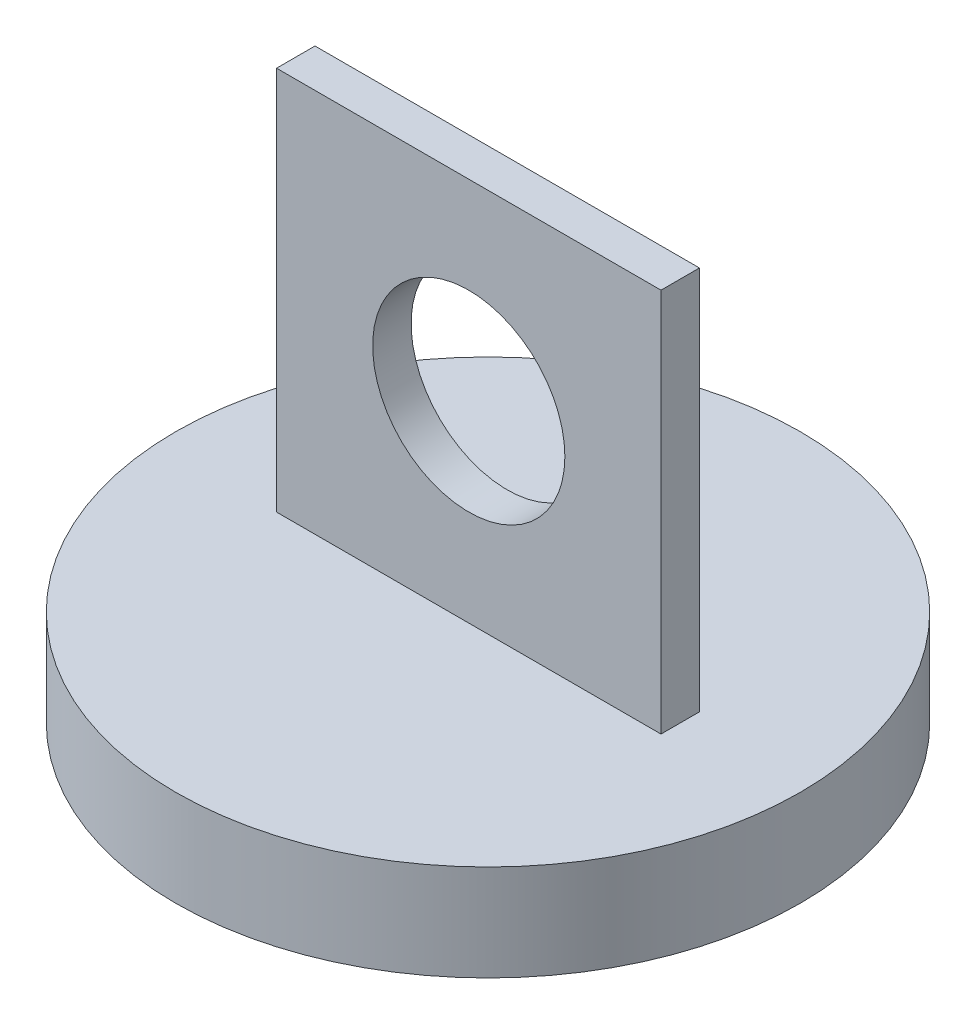
SolidWorks part; units mm, degrees
ref_plane "Front Plane" through (0, 0, 0) normal (0, 0, 1) x (1, 0, 0)
ref_plane "Top Plane" through (0, 0, 0) normal (0, 1, 0) x (1, 0, 0)
ref_plane "Right Plane" through (0, 0, 0) normal (1, 0, 0) x (0, 0, -1)
sketch "Sketch1" plane through (0, 0, 0) normal (0, 1, 0) x (1, 0, 0)
  line L2 (-32.5, 0) -> (75, 0) construction
  circle A1 centre (0, 0) radius 32.5
  dimension "D2" = 65
extrude "Boss-Extrude1" add sketch "Sketch1" along normal blind 10
sketch "Sketch4" plane through (0, 10, 0) normal (0, 1, 0) x (1, 0, 0)
  line L0 (20, 2) -> (-20, 2)
  line L1 (20, 2) -> (20, -2)
  line L2 (20, -2) -> (-20, -2)
  line L3 (-20, 2) -> (-20, -2)
  line L4 (20, 2) -> (-20, -2) construction
  line L5 (20, -2) -> (-20, 2) construction
  point P0 (0, 0)
  dimension "D1" = 4
  dimension "D2" = 40
extrude "Boss-Extrude3" add sketch "Sketch4" along normal blind 40
sketch "Sketch5" plane through (0, 0, 2) normal (0, 0, 1) x (1, 0, 0)
  line L0 (-20, 50) -> (20, 50) construction
  line L1 (20, 50) -> (20, 10) construction
  circle A0 centre (0, 30) radius 10
  point P5 (0, 50)
  point P8 (20, 30)
  dimension "D1" = 20
extrude "Cut-Extrude2" cut sketch "Sketch5" against normal blind 40
